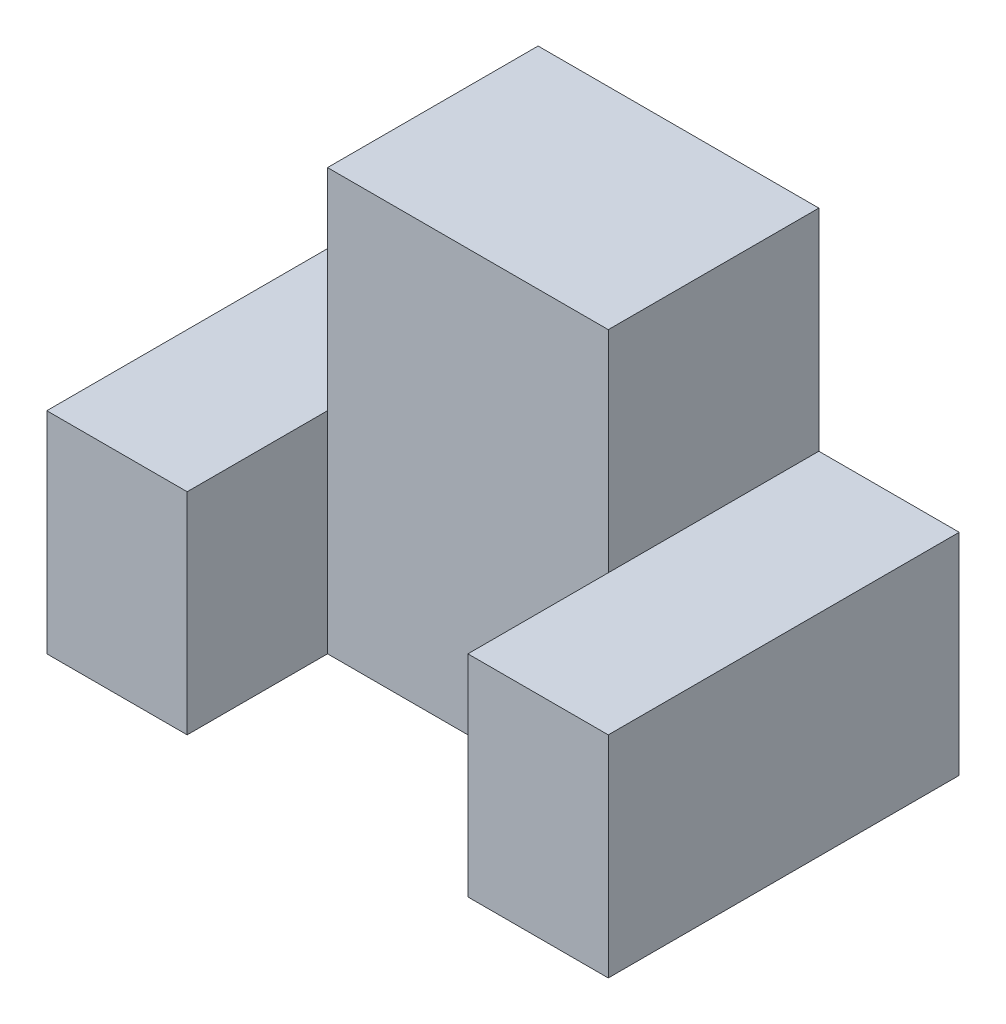
SolidWorks part; units mm, degrees
ref_plane "Alzado" through (0, 0, 0) normal (0, 0, 1) x (1, 0, 0)
ref_plane "Planta" through (0, 0, 0) normal (0, 1, 0) x (1, 0, 0)
ref_plane "Vista lateral" through (0, 0, 0) normal (1, 0, 0) x (0, 0, -1)
sketch "Croquis2" plane through (0, 0, 0) normal (0, 0, 1) x (1, 0, 0)
  line L1 (-20, -30) -> (20, -30)
  line L2 (-20, -30) -> (-20, 30)
  line L3 (-20, 30) -> (20, 30)
  line L4 (20, -30) -> (20, 30)
  line L5 (-20, -30) -> (20, 30) construction
  line L6 (-20, 30) -> (20, -30) construction
  point P0 (0, 0)
  dimension "D1" = 60
  dimension "D2" = 40
extrude "Saliente-Extruir1" add sketch "Croquis2" along normal blind 30
sketch "Croquis3" plane through (20, 0, 0) normal (1, 0, 0) x (0, 0, -1)
  line L1 (0, -30) -> (-50, -30)
  line L2 (0, -30) -> (0, 0)
  line L3 (0, 0) -> (-50, 0)
  line L4 (-50, -30) -> (-50, 0)
  dimension "D1" = 30
  dimension "D2" = 50
sketch "Croquis4" plane through (-20, 0, 0) normal (-1, 0, 0) x (0, 0, 1)
  line L1 (0, -30) -> (50, -30)
  line L2 (0, -30) -> (0, 0)
  line L3 (0, 0) -> (50, 0)
  line L4 (50, -30) -> (50, 0)
extrude "Saliente-Extruir2" add sketch "Croquis3" along normal blind 20
extrude "Saliente-Extruir3" add sketch "Croquis4" along normal blind 20
sketch "Croquis6" plane through (0, 0, 30) normal (0, 0, 1) x (1, 0, 0)
  line L0 (-20, 15) -> (20, 15) construction
  line L1 (-20, 30) -> (-20, 0) construction
  line L2 (20, 0) -> (20, 30) construction
  text T0 "SOLIDWORKS \r\n2026\r\nBENJAMIN :)"
